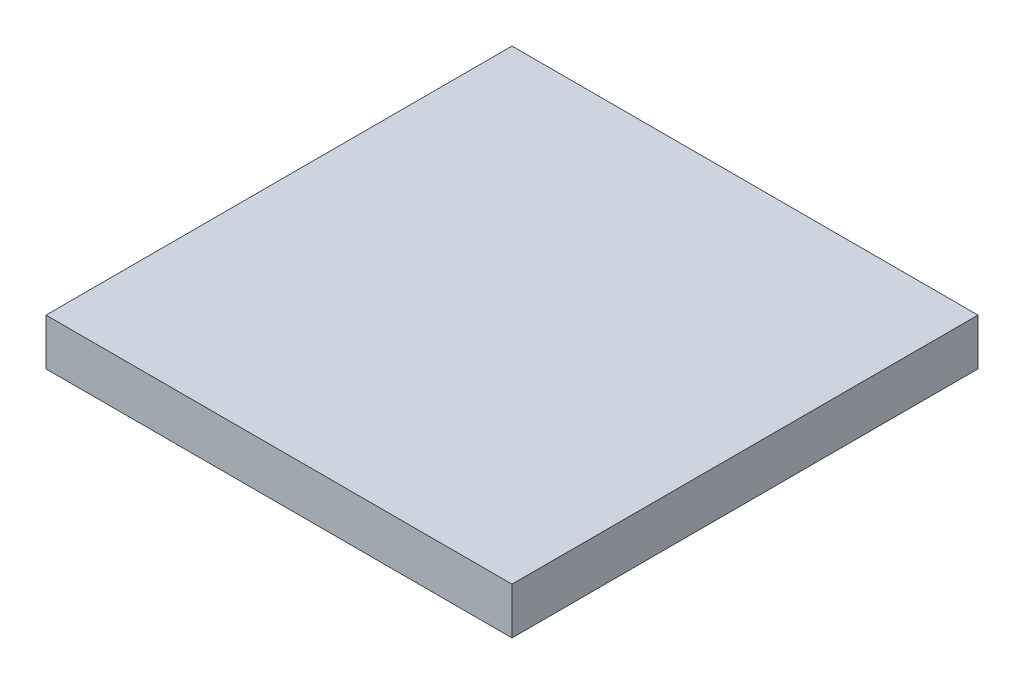
SolidWorks part; units mm, degrees
ref_plane "Front Plane" through (0, 0, 0) normal (0, 0, 1) x (1, 0, 0)
ref_plane "Top Plane" through (0, 0, 0) normal (0, 1, 0) x (1, 0, 0)
ref_plane "Right Plane" through (0, 0, 0) normal (1, 0, 0) x (0, 0, -1)
sketch "Sketch1" plane through (0, 0, 0) normal (0, 1, 0) x (1, 0, 0)
  line L1 (-15, 15) -> (15, 15)
  line L2 (-15, 15) -> (-15, -15)
  line L3 (-15, -15) -> (15, -15)
  line L4 (15, 15) -> (15, -15)
  line L5 (-15, 15) -> (15, -15) construction
  line L6 (-15, -15) -> (15, 15) construction
  point P0 (0, 0)
  dimension "D1" = 30
  dimension "D2" = 30
extrude "Boss-Extrude1" add sketch "Sketch1" along normal blind 3
